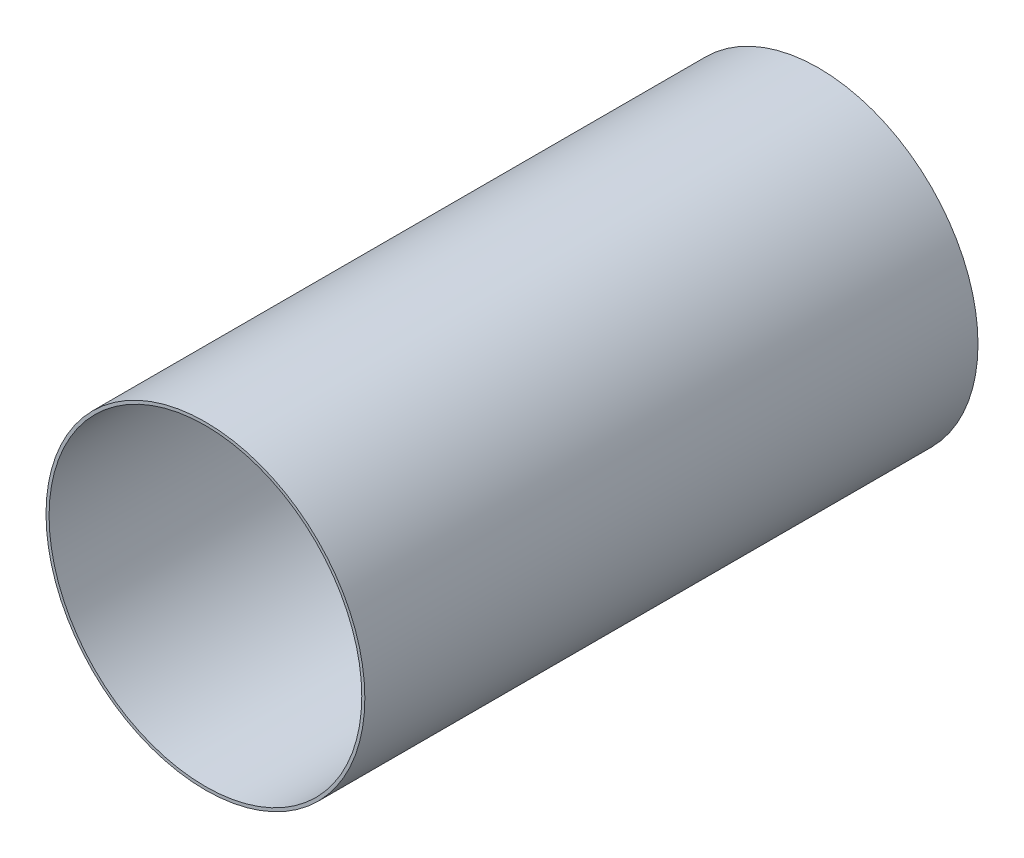
SolidWorks part; units mm, degrees
ref_plane "정면" through (0, 0, 0) normal (0, 0, 1) x (1, 0, 0)
ref_plane "윗면" through (0, 0, 0) normal (0, 1, 0) x (1, 0, 0)
ref_plane "우측면" through (0, 0, 0) normal (1, 0, 0) x (0, 0, -1)
sketch "스케치1" plane through (0, 0, 0) normal (0, 0, 1) x (1, 0, 0)
  circle A0 centre (0, 0) radius 2.55
  circle A1 centre (0, 0) radius 2.6
  dimension "D1" = 5.1
  dimension "D2" = 5.2
extrude "보스-돌출1" add sketch "스케치1" along normal blind 10
